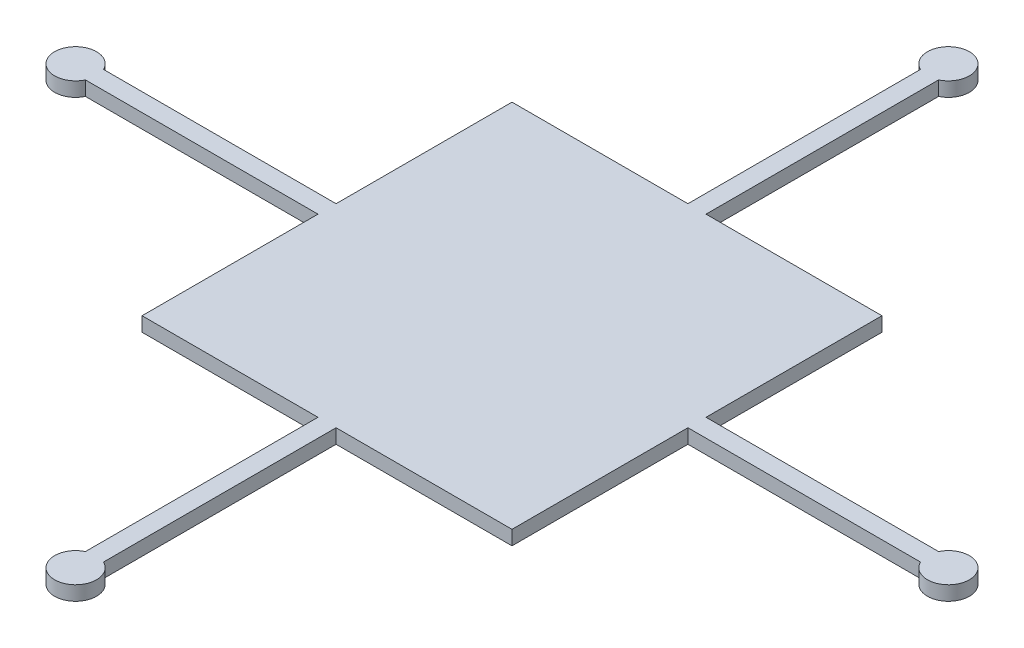
SolidWorks part; units mm, degrees
ref_plane "Front Plane" through (0, 0, 0) normal (0, 0, 1) x (1, 0, 0)
ref_plane "Top Plane" through (0, 0, 0) normal (0, 1, 0) x (1, 0, 0)
ref_plane "Right Plane" through (0, 0, 0) normal (1, 0, 0) x (0, 0, -1)
sketch "Sketch1" plane through (0, 0, 0) normal (0, 1, 0) x (1, 0, 0)
  line L0 (-114.3056, 0) -> (122.688, 0) construction
  line L1 (0, 86.1102) -> (0, -75.0607) construction
  line L2 (34.356, 0) -> (65.5061, 0)
  line L3 (0, 0) -> (31.1501, 0)
  line L4 (0, 0) -> (0, 31.1501)
  line L5 (0, 65.5061) -> (31.1501, 65.5061)
  line L6 (65.5061, 0) -> (65.5061, 31.1501)
  line L7 (0, 32.7531) -> (65.5061, 32.7531) construction
  line L8 (31.1501, 0) -> (31.1501, -41.1753)
  line L9 (32.7531, 0) -> (32.7531, 65.5061) construction
  line L10 (34.356, 0) -> (34.356, -41.1753)
  line L11 (34.356, 65.5061) -> (34.356, 106.6814)
  line L12 (31.1501, 65.5061) -> (31.1501, 106.6814)
  line L13 (0, 65.5061) -> (65.5061, 0) construction
  line L14 (65.5061, 31.1501) -> (106.6814, 31.1501)
  line L15 (65.5061, 34.356) -> (106.6814, 34.356)
  line L16 (0, 34.356) -> (-41.1753, 34.356)
  line L17 (0, 31.1501) -> (-41.1753, 31.1501)
  line L18 (0, 34.356) -> (0, 65.5061)
  line L19 (34.356, 65.5061) -> (65.5061, 65.5061)
  line L20 (65.5061, 34.356) -> (65.5061, 65.5061)
  arc A0 (31.1501, -41.1753) -> (34.356, -41.1753) centre (32.7531, -44.5211) ccw
  circle A1 centre (32.7531, -44.5211) radius 3.71 construction
  circle A2 centre (32.7531, -44.5211) radius 3.71 construction
  circle A3 centre (32.7531, 110.0272) radius 3.71 construction
  arc A4 (31.1501, 106.6814) -> (34.356, 106.6814) centre (32.7531, 110.0272) cw
  circle A5 centre (110.0272, 32.7531) radius 3.71 construction
  arc A6 (106.6814, 34.356) -> (106.6814, 31.1501) centre (110.0272, 32.7531) cw
  circle A7 centre (-44.5211, 32.7531) radius 3.71 construction
  arc A8 (-41.1753, 34.356) -> (-41.1753, 31.1501) centre (-44.5211, 32.7531) ccw
  circle A9 centre (-28.1259, 16.3799) radius 3.71 construction
  circle A10 centre (-28.1259, 16.3799) radius 3.71 construction
  point P41 (-166.2932, 21.1298)
extrude "Boss-Extrude1" add sketch "Sketch1" along normal blind 2.54
